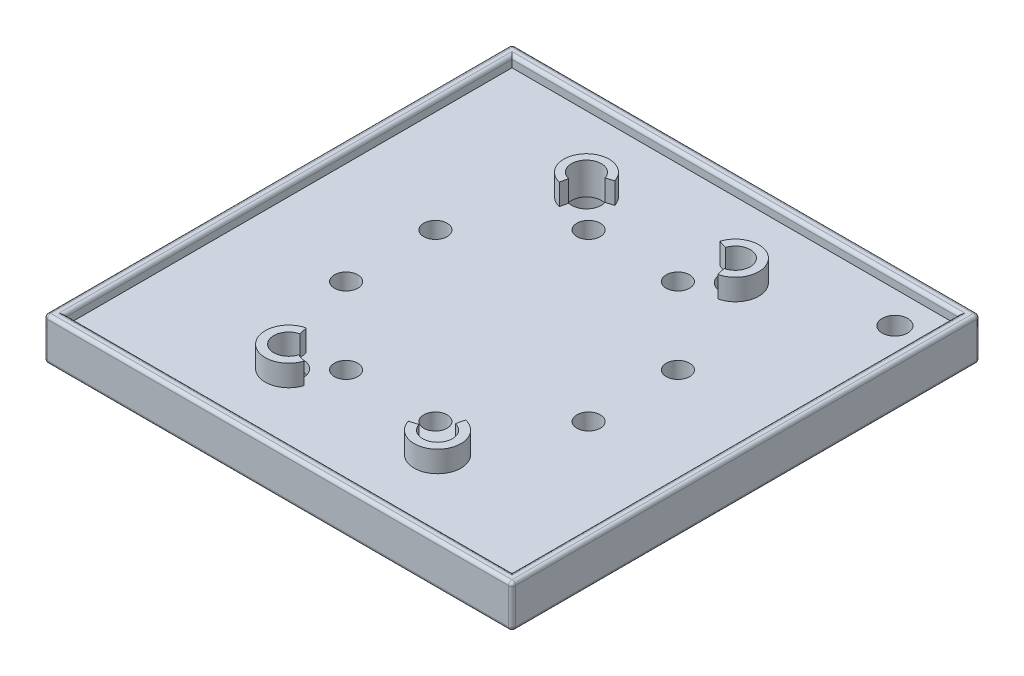
SolidWorks part; units mm, degrees
ref_plane "Front Plane" through (0, 0, 0) normal (0, 0, 1) x (1, 0, 0)
ref_plane "Top Plane" through (0, 0, 0) normal (0, 1, 0) x (1, 0, 0)
ref_plane "Right Plane" through (0, 0, 0) normal (1, 0, 0) x (0, 0, -1)
sketch "Sketch1" plane through (0, 0, 0) normal (0, 1, 0) x (1, 0, 0)
  line L1 (-47.7358, 37.9811) -> (62.2642, 37.9811)
  line L2 (-47.7358, 37.9811) -> (-47.7358, -72.0189)
  line L3 (-47.7358, -72.0189) -> (62.2642, -72.0189)
  line L4 (62.2642, 37.9811) -> (62.2642, -72.0189)
  dimension "D1" = 110
  dimension "D2" = 110
extrude "Boss-Extrude1" add sketch "Sketch1" along normal blind 10 contours L1 L4 L3 L2
sketch "Sketch2" plane through (0, 10, 0) normal (0, 1, 0) x (1, 0, 0)
  line L0 (-47.7358, 37.9811) -> (-47.7358, -72.0189) construction
  line L1 (-45.2358, 35.4811) -> (59.7642, 35.4811)
  line L2 (-45.2358, 35.4811) -> (-45.2358, -69.5189)
  line L3 (-45.2358, -69.5189) -> (59.7642, -69.5189)
  line L4 (59.7642, 35.4811) -> (59.7642, -69.5189)
  line L5 (-47.7358, 37.9811) -> (62.2642, 37.9811) construction
  dimension "D1" = 105
  dimension "D2" = 105
  dimension "D3" = 2.5
  dimension "D4" = 2.5
extrude "Cut-Extrude1" cut sketch "Sketch2" against normal blind 2.5 and the other way blind 1 contours L1 L4 L3 L2
sketch "Sketch5" plane through (0, 7.5, 0) normal (0, 1, 0) x (1, 0, 0)
  line L0 (-45.2358, 35.4811) -> (-45.2358, -69.5189) construction
  line L1 (-45.2358, 35.4811) -> (59.7642, 35.4811) construction
  line L2 (59.7642, 35.4811) -> (59.7642, -69.5189) construction
  line L3 (-45.2358, 35.4811) -> (-45.2358, -69.5189) construction
  line L4 (-45.2358, -69.5189) -> (59.7642, -69.5189) construction
  circle A0 centre (-3.2358, 11.4811) radius 2.75
  circle A1 centre (17.7642, 11.4811) radius 2.75
  circle A2 centre (-3.2358, -45.5189) radius 2.75
  circle A3 centre (17.7642, -45.5189) radius 2.75
  circle A4 centre (-21.2358, -6.5189) radius 2.75
  circle A5 centre (-21.2358, -27.5189) radius 2.75
  circle A6 centre (35.7642, -6.5189) radius 2.75
  circle A7 centre (35.7642, -27.5189) radius 2.75
  dimension "D1" = 42
  dimension "D2" = 24
  dimension "D3" = 42
  dimension "D4" = 81
  dimension "D5" = 24
  dimension "D6" = 42
  dimension "D7" = 42
  dimension "D8" = 24
  dimension "D9" = 42
extrude "Cut-Extrude2" cut sketch "Sketch5" against normal blind 10 contours A1 | A2 | A0 | A3 | A6 | A7 | A5 | A4
sketch "Sketch6" plane through (0, 7.5, 0) normal (0, 1, 0) x (1, 0, 0)
  line L0 (-45.2358, 35.4811) -> (-45.2358, -69.5189) construction
  line L1 (-45.2358, 35.4811) -> (59.7642, 35.4811) construction
  circle A0 centre (-10.2358, 17.9811) radius 3.5
  circle A1 centre (24.7642, 17.9811) radius 3.5
  circle A2 centre (-10.2358, -52.0189) radius 3.5
  circle A3 centre (24.7642, -52.0189) radius 3.5
  point P2 (7.2642, 20.403)
  point P6 (-23.4564, -17.0189)
  dimension "D1" = 52.5
  dimension "D2" = 17.5
  dimension "D3" = 52.5
  dimension "D4" = 35
  dimension "D5" = 17.5
  dimension "D6" = 35
extrude "Cut-Extrude3" cut sketch "Sketch6" against normal blind 12.5
sketch "Sketch8" plane through (0, 7.5, 0) normal (0, 1, 0) x (1, 0, 0)
  line L0 (24.7642, 17.9811) -> (17.7642, 11.4811) construction
  line L1 (19.5078, 19.6003) -> (21.4193, 19.0115)
  line L3 (25.9901, 12.6194) -> (25.5443, 14.5692)
  arc A0 (19.5078, 19.6003) -> (25.9901, 12.6194) centre (24.7642, 17.9811) cw
  circle A1 centre (24.7642, 17.9811) radius 3.5 construction
  arc A3 (21.4193, 19.0115) -> (25.5443, 14.5692) centre (24.7642, 17.9811) cw
  point P0 (17.7642, 11.4811)
  point P11 (24.7642, 17.9811)
  dimension "D1" = 60
  dimension "D2" = 60
extrude "Boss-Extrude2" add sketch "Sketch8" along normal blind 5
sketch "Sketch15" plane through (0, 7.5, 0) normal (0, 1, 0) x (1, 0, 0)
  line L0 (-3.2358, 11.4811) -> (-10.2358, 17.9811) construction
  line L1 (-3.2358, -45.5189) -> (-10.2358, -52.0189) construction
  line L2 (24.7642, -52.0189) -> (17.7642, -45.5189) construction
  line L3 (-11.4224, 12.7915) -> (-11.016, 14.5692)
  line L5 (-5.1482, 19.5484) -> (-6.891, 19.0115)
  line L6 (-11.4618, -46.6572) -> (-11.016, -48.6069)
  line L7 (-6.891, -53.0492) -> (-4.9796, -53.638)
  line L8 (-10.2358, -52.0189) -> (-4.9796, -53.638) construction
  line L9 (19.5079, -53.638) -> (21.4193, -53.0492)
  line L10 (24.7642, -52.0189) -> (19.5079, -53.638) construction
  line L11 (24.7642, -52.0189) -> (25.9901, -46.6572) construction
  line L12 (25.5443, -48.6069) -> (25.9901, -46.6572)
  arc A0 (-11.4224, 12.7915) -> (-5.1482, 19.5484) centre (-10.2358, 17.9811) cw
  circle A1 centre (-10.2358, 17.9811) radius 3.5 construction
  arc A2 (-11.016, 14.5692) -> (-6.891, 19.0115) centre (-10.2358, 17.9811) cw
  arc A3 (-6.891, -53.0492) -> (-11.016, -48.6069) centre (-10.2358, -52.0189) cw
  circle A4 centre (-10.2358, -52.0189) radius 3.5 construction
  arc A5 (-4.9796, -53.638) -> (-11.4618, -46.6572) centre (-10.2358, -52.0189) cw
  arc A6 (25.9901, -46.6572) -> (19.5079, -53.638) centre (24.7642, -52.0189) cw
  arc A7 (25.5443, -48.6069) -> (21.4193, -53.0492) centre (24.7642, -52.0189) cw
  circle A8 centre (24.7642, -52.0189) radius 3.5 construction
  point P8 (17.7642, -45.5189)
  point P9 (24.7642, -52.0189)
  point P10 (-7.8008, 20.4952)
  dimension "D2" = 60
  dimension "D4" = 180
  dimension "D5" = 60
  dimension "D1" = 60
  dimension "D3" = 60
  dimension "D6" = 60
  dimension "D7" = 0
  dimension "D8" = 0
extrude "Boss-Extrude3" add sketch "Sketch15" along normal blind 5
sketch "Sketch20" plane through (0, 0, 0) normal (0, -1, 0) x (1, 0, 0)
  circle A0 centre (-10.2358, 52.0189) radius 6
  circle A1 centre (-10.2358, -17.9811) radius 6
  circle A2 centre (24.7642, -17.9811) radius 6
  circle A3 centre (24.7642, 52.0189) radius 6
  circle A4 centre (-10.2358, 52.0189) radius 3.5
  circle A5 centre (24.7642, 52.0189) radius 3.5
  circle A6 centre (-10.2358, -17.9811) radius 3.5
  circle A7 centre (24.7642, -17.9811) radius 3.5
extrude "Cut-Extrude5" cut sketch "Sketch20" against normal blind 5
fillet "Fillet1" radius 0.8 16 edges at (59.7642, 10, 17.0189) (7.2642, 10, -35.4811) (-45.2358, 10, 17.0189) (7.2642, 10, 69.5189) (-47.7358, 10, 17.0189) (-47.7358, 5, 72.0189) (7.2642, 10, 72.0189) (62.2642, 5, 72.0189) (62.2642, 10, 17.0189) (62.2642, 5, -37.9811) (7.2642, 10, -37.9811) (-47.7358, 5, -37.9811) (7.2642, 0, 72.0189) (62.2642, 0, 17.0189) (7.2642, 0, -37.9811) (-47.7358, 0, 17.0189)
sketch "Sketch23" plane through (0, 7.5, 0) normal (0, 1, 0) x (1, 0, 0)
  line L0 (-46.9358, 37.9811) -> (61.4642, 37.9811) construction
  line L1 (62.2642, 37.1811) -> (62.2642, -71.2189) construction
  circle A0 centre (52.2642, 27.9811) radius 3
  dimension "D1" = 10
  dimension "D2" = 10
extrude "Cut-Extrude6" cut sketch "Sketch23" against normal blind 10
